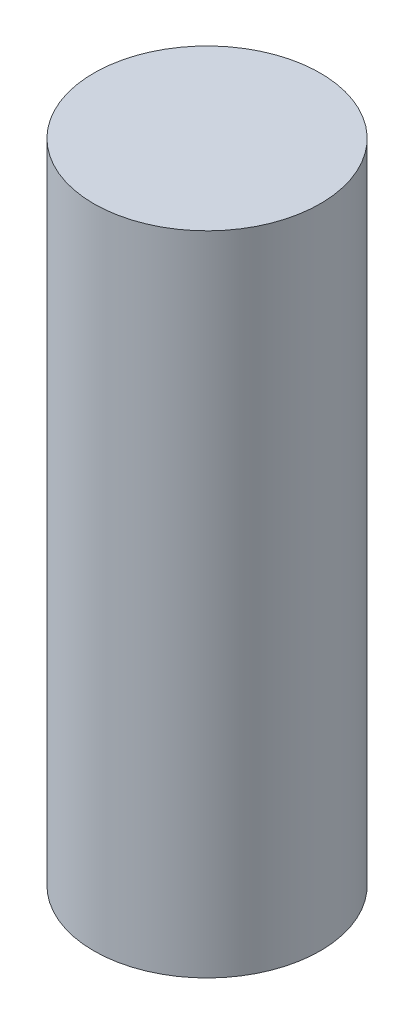
SolidWorks part; units mm, degrees
ref_plane "Front Plane" through (0, 0, 0) normal (0, 0, 1) x (1, 0, 0)
ref_plane "Top Plane" through (0, 0, 0) normal (0, 1, 0) x (1, 0, 0)
ref_plane "Right Plane" through (0, 0, 0) normal (1, 0, 0) x (0, 0, -1)
sketch "Sketch1" plane through (0, 0, 0) normal (0, 1, 0) x (1, 0, 0)
  circle A0 centre (0, 0) radius 35.56
  dimension "D1" = 71.12
extrude "Boss-Extrude1" add sketch "Sketch1" along normal mid plane 203.2
